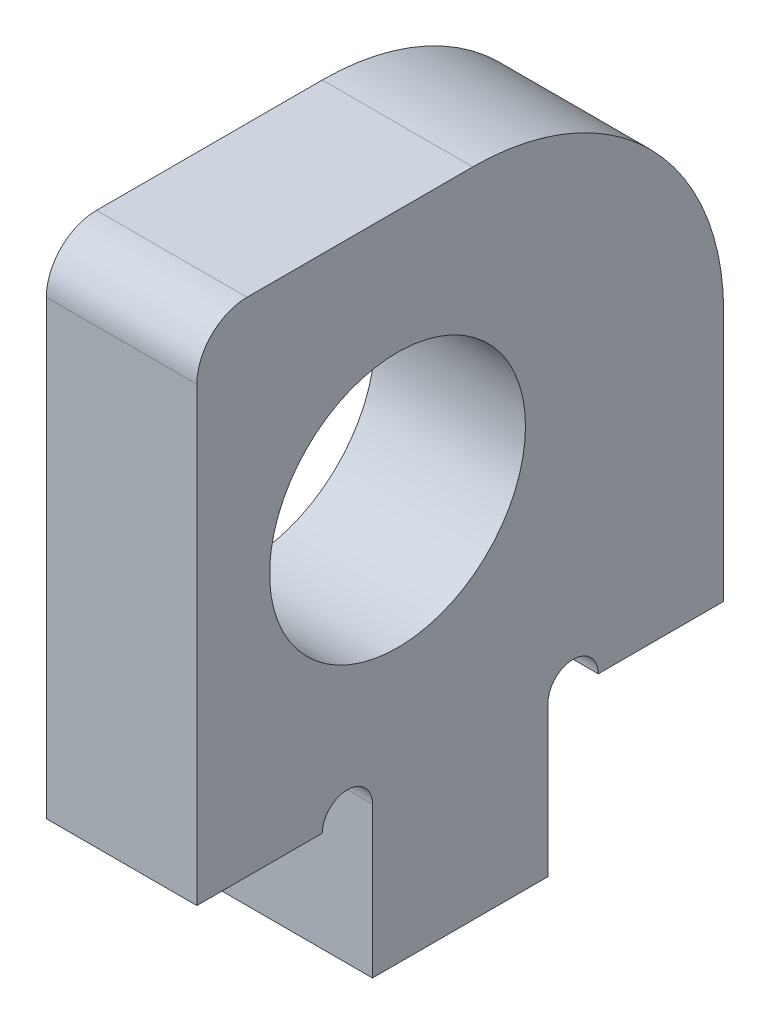
SolidWorks part; units mm, degrees
ref_plane "정면" through (0, 0, 0) normal (0, 0, 1) x (1, 0, 0)
ref_plane "윗면" through (0, 0, 0) normal (0, 1, 0) x (1, 0, 0)
ref_plane "우측면" through (0, 0, 0) normal (1, 0, 0) x (0, 0, -1)
sketch "스케치1" plane through (0, 0, 0) normal (1, 0, 0) x (0, 0, -1)
  line L0 (0, 0) -> (0, 20)
  line L1 (0, 0) -> (21, 0)
  line L2 (0, 20) -> (21, 20)
  line L3 (21, 20) -> (21, 0)
  circle A1 centre (8, 10) radius 5.1
  dimension "D1" = 10.2
  dimension "D5" = 21
  dimension "D2" = 20
  dimension "D3" = 8
  dimension "D4" = 10
extrude "보스-돌출1" add sketch "스케치1" along normal blind 6
fillet "필렛1" radius 10 1 edges at (3, 20, -21)
fillet "필렛2" radius 2 1 edges at (3, 20, 0)
sketch "스케치2" plane through (6, 0, 0) normal (1, 0, 0) x (0, 0, -1)
  line L0 (0, 0) -> (21, 0) construction
  line L1 (7, 0) -> (14, 0)
  line L2 (7, 0) -> (7, -6)
  line L3 (7, -6) -> (14, -6)
  line L4 (14, 0) -> (14, -6)
  line L5 (7, -6) -> (0, -6) construction
  line L6 (0, -6) -> (0, 0) construction
  line L7 (14, -6) -> (21, -6) construction
  line L8 (21, -6) -> (21, 0) construction
  dimension "D1" = 6
extrude "보스-돌출2" add sketch "스케치2" against normal blind 6
sketch "스케치3" plane through (6, 0, 0) normal (1, 0, 0) x (0, 0, -1)
  line L0 (14, 0) -> (21, 0) construction
  line L1 (0, 0) -> (7, 0) construction
  circle A0 centre (15, 0) radius 1
  circle A1 centre (6, 0) radius 1
  dimension "D1" = 2
extrude "컷-돌출1" cut sketch "스케치3" against normal blind 10
